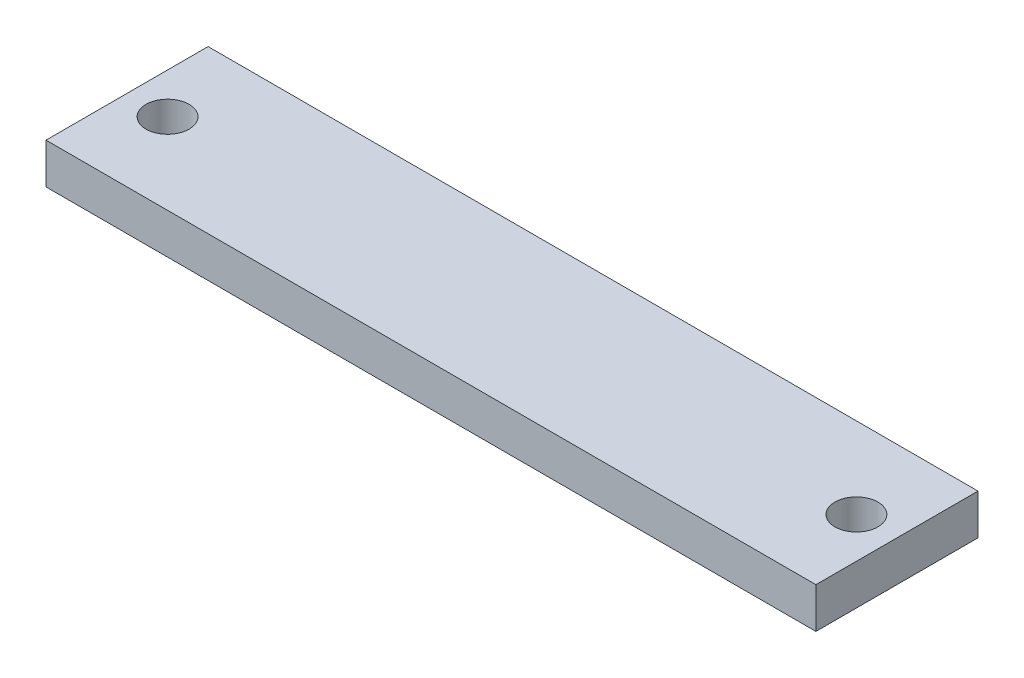
SolidWorks part; units mm, degrees
ref_plane "Front Plane" through (0, 0, 0) normal (0, 0, 1) x (1, 0, 0)
ref_plane "Top Plane" through (0, 0, 0) normal (0, 1, 0) x (1, 0, 0)
ref_plane "Right Plane" through (0, 0, 0) normal (1, 0, 0) x (0, 0, -1)
sketch "Sketch1" plane through (0, 0, 0) normal (0, 1, 0) x (1, 0, 0)
  line L1 (-120.65, -25.4) -> (120.65, -25.4)
  line L2 (-120.65, -25.4) -> (-120.65, 25.4)
  line L3 (-120.65, 25.4) -> (120.65, 25.4)
  line L4 (120.65, -25.4) -> (120.65, 25.4)
  line L5 (-120.65, -25.4) -> (120.65, 25.4) construction
  line L6 (-120.65, 25.4) -> (120.65, -25.4) construction
  point P0 (0, 0)
  dimension "D1" = 50.8
  dimension "D2" = 241.3
extrude "Boss-Extrude1" add sketch "Sketch1" along normal blind 12.7
hole_wizard "1/2 Clearance Hole1" positions "Sketch9" profile "Sketch8" hole size "1/2" standard "ANSI Inch" end condition through all
sketch "Sketch9" plane through (0, 12.7, 0) normal (0, 1, 0) x (1, 0, 0)
  line L0 (0, 0) -> (-107.95, 0) construction
  line L2 (0, 0) -> (107.95, 0) construction
  point P0 (-107.95, 0)
  point P2 (107.95, 0)
  dimension "D1" = 107.95
sketch "Sketch8" plane through (-107.95, 12.7, 0) normal (1, 0, 0) x (0, 0, 1)
  line L0 (0, 0) -> (0, 12.7)
  line L1 (0, 12.7) -> (6.7462, 12.7)
  line L2 (6.7462, 12.7) -> (6.7462, 0)
  line L5 (6.7462, 0) -> (0, 0)
  line L11 (0, -6.35) -> (0, 107.95) construction
  dimension "Thru Hole Dia." = 13.4925
  dimension "Thru Hole Depth" = 12.7
